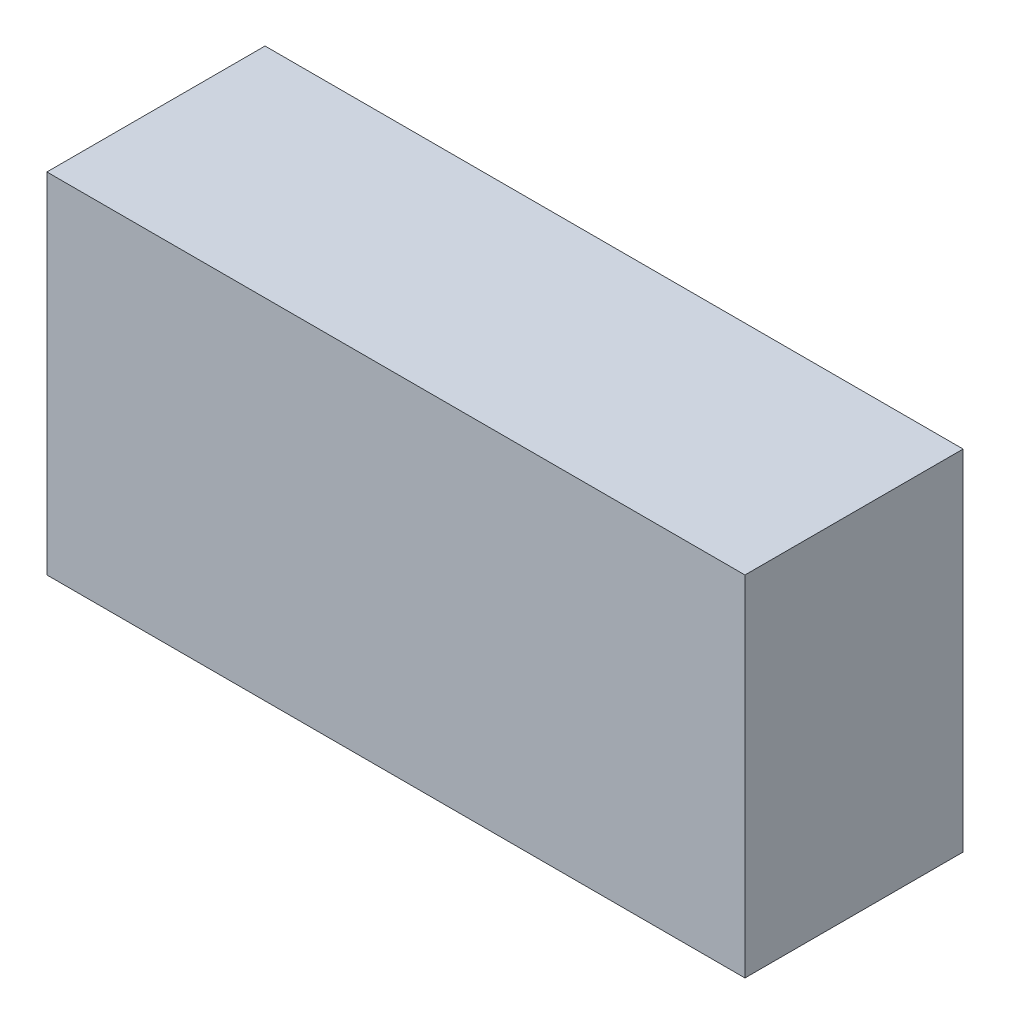
SolidWorks part; units mm, degrees
ref_plane "Front Plane" through (0, 0, 0) normal (0, 0, 1) x (1, 0, 0)
ref_plane "Top Plane" through (0, 0, 0) normal (0, 1, 0) x (1, 0, 0)
ref_plane "Right Plane" through (0, 0, 0) normal (1, 0, 0) x (0, 0, -1)
sketch "Sketch1" plane through (0, 0, 0) normal (0, 0, 1) x (1, 0, 0)
  line L1 (-0.8, 0.4) -> (0.8, 0.4)
  line L2 (-0.8, 0.4) -> (-0.8, -0.4)
  line L3 (-0.8, -0.4) -> (0.8, -0.4)
  line L4 (0.8, 0.4) -> (0.8, -0.4)
  line L5 (-0.8, 0.4) -> (0.8, -0.4) construction
  line L6 (-0.8, -0.4) -> (0.8, 0.4) construction
  point P0 (0, 0)
  dimension "D1" = 0.8
  dimension "D2" = 1.6
extrude "Boss-Extrude1" add sketch "Sketch1" along normal blind 0.5
